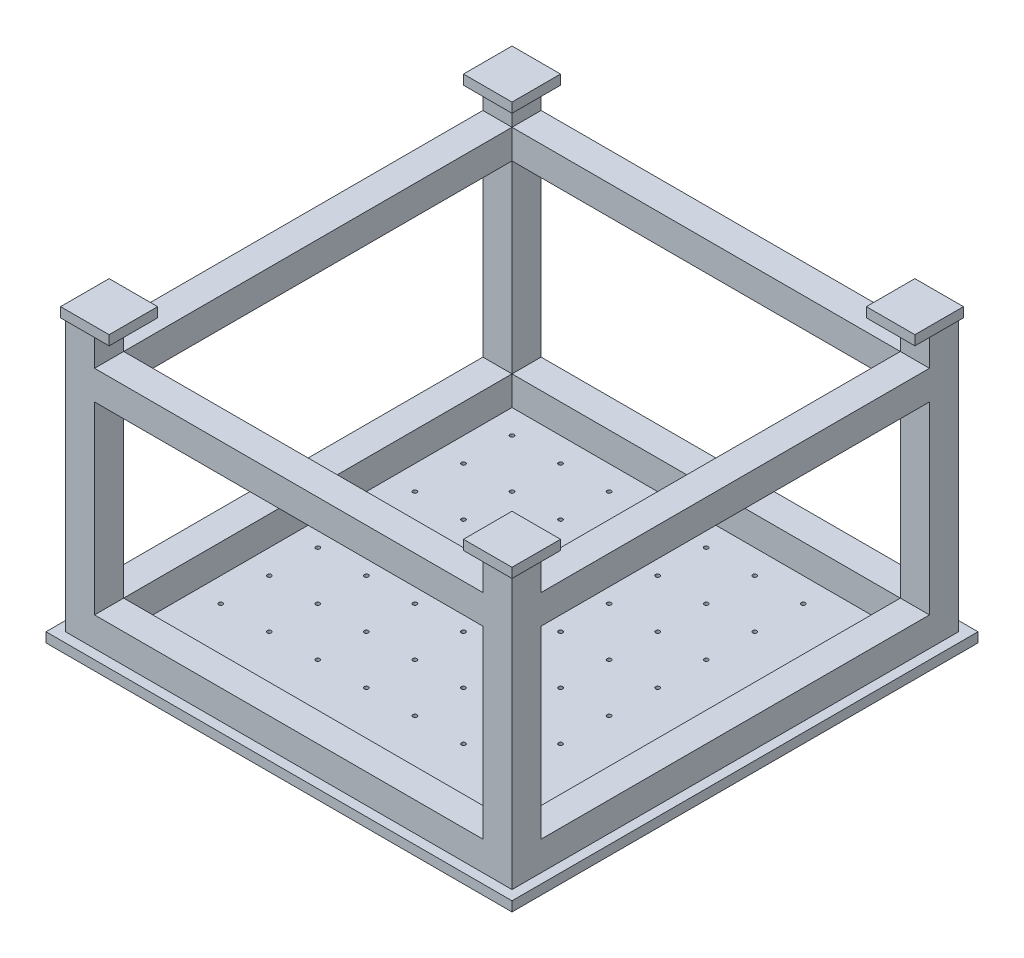
SolidWorks part; units mm, degrees
ref_plane "Front Plane" through (0, 0, 0) normal (0, 0, 1) x (1, 0, 0)
ref_plane "Top Plane" through (0, 0, 0) normal (0, 1, 0) x (1, 0, 0)
ref_plane "Right Plane" through (0, 0, 0) normal (1, 0, 0) x (0, 0, -1)
sketch "Sketch1" plane through (0, 0, 0) normal (0, 1, 0) x (1, 0, 0)
  line L0 (0, 609.6) -> (1219.2, 609.6) construction
  line L1 (0, 0) -> (1219.2, 0)
  line L2 (0, 0) -> (0, 1219.2)
  line L3 (0, 1219.2) -> (1219.2, 1219.2)
  line L4 (1219.2, 0) -> (1219.2, 1219.2)
  dimension "D1" = 1219.2
  dimension "D2" = 1219.2
extrude "Boss-Extrude1" add sketch "Sketch1" along normal blind 25.4
sketch "Sketch2" plane through (0, 25.4, 0) normal (0, 1, 0) x (1, 0, 0)
  line L0 (1219.2, 1219.2) -> (0, 1219.2) construction
  line L1 (25.4, 1193.8) -> (101.6, 1193.8)
  line L2 (25.4, 1193.8) -> (25.4, 1117.6)
  line L3 (25.4, 1117.6) -> (101.6, 1117.6)
  line L4 (101.6, 1193.8) -> (101.6, 1117.6)
  line L5 (0, 1219.2) -> (0, 0) construction
  line L6 (609.6, 1219.2) -> (609.6, 0) construction
  line L7 (-156.4826, 0) -> (156.4826, 0) construction
  line L8 (0, 609.6) -> (1219.2, 609.6) construction
  line L9 (1219.2, 0) -> (1219.2, 1219.2) construction
  line L10 (1117.6, 1193.8) -> (1117.6, 1117.6)
  line L11 (1193.8, 1117.6) -> (1117.6, 1117.6)
  line L12 (1193.8, 1193.8) -> (1193.8, 1117.6)
  line L13 (1193.8, 1193.8) -> (1117.6, 1193.8)
  line L14 (1193.8, 25.4) -> (1117.6, 25.4)
  line L15 (1193.8, 25.4) -> (1193.8, 101.6)
  line L16 (1193.8, 101.6) -> (1117.6, 101.6)
  line L17 (1117.6, 25.4) -> (1117.6, 101.6)
  line L18 (101.6, 25.4) -> (101.6, 101.6)
  line L19 (25.4, 101.6) -> (101.6, 101.6)
  line L20 (25.4, 25.4) -> (25.4, 101.6)
  line L21 (25.4, 25.4) -> (101.6, 25.4)
  dimension "D1" = 76.2
  dimension "D2" = 76.2
  dimension "D3" = 25.4
  dimension "D4" = 25.4
extrude "Boss-Extrude2" add sketch "Sketch2" along normal blind 711.2
sketch "Sketch3" plane through (0, 0, -101.6) normal (0, 0, -1) x (-1, 0, 0)
  line L0 (-101.6, 736.6) -> (-101.6, 25.4) construction
  line L1 (-25.4, 25.4) -> (-101.6, 25.4)
  line L2 (-25.4, 25.4) -> (-25.4, 101.6)
  line L3 (-25.4, 101.6) -> (-101.6, 101.6)
  line L4 (-101.6, 25.4) -> (-101.6, 101.6)
  line L5 (-1193.8, 736.6) -> (-1193.8, 25.4) construction
  line L6 (-1117.6, 25.4) -> (-1193.8, 25.4)
  line L7 (-1117.6, 25.4) -> (-1117.6, 101.6)
  line L8 (-1117.6, 101.6) -> (-1193.8, 101.6)
  line L9 (-1193.8, 25.4) -> (-1193.8, 101.6)
  line L10 (-25.4, 736.6) -> (-25.4, 25.4) construction
  line L11 (-25.4, 584.2) -> (-101.6, 584.2)
  line L12 (-25.4, 584.2) -> (-25.4, 660.4)
  line L13 (-25.4, 660.4) -> (-101.6, 660.4)
  line L14 (-101.6, 584.2) -> (-101.6, 660.4)
  line L15 (-1117.6, 736.6) -> (-1117.6, 25.4) construction
  line L16 (-1117.6, 584.2) -> (-1193.8, 584.2)
  line L17 (-1117.6, 584.2) -> (-1117.6, 660.4)
  line L18 (-1117.6, 660.4) -> (-1193.8, 660.4)
  line L19 (-1193.8, 584.2) -> (-1193.8, 660.4)
  line L20 (-101.6, 736.6) -> (-25.4, 736.6) construction
  dimension "D1" = 76.2
  dimension "D2" = 76.2
  dimension "D3" = 76.2
extrude "Boss-Extrude3" add sketch "Sketch3" along normal up to next
sketch "Sketch4" plane through (1117.6, 0, 0) normal (-1, 0, 0) x (0, 0, 1)
  line L0 (-1117.6, 101.6) -> (-101.6, 101.6) construction
  line L1 (-25.4, 25.4) -> (-101.6, 25.4)
  line L2 (-25.4, 25.4) -> (-25.4, 101.6)
  line L3 (-25.4, 101.6) -> (-101.6, 101.6)
  line L4 (-101.6, 25.4) -> (-101.6, 101.6)
  line L5 (-1193.8, 25.4) -> (-1117.6, 25.4)
  line L6 (-1193.8, 25.4) -> (-1193.8, 101.6)
  line L7 (-1193.8, 101.6) -> (-1117.6, 101.6)
  line L8 (-1117.6, 25.4) -> (-1117.6, 101.6)
  line L9 (-25.4, 736.6) -> (-25.4, 25.4) construction
  line L10 (-101.6, 584.2) -> (-25.4, 584.2)
  line L11 (-101.6, 584.2) -> (-101.6, 660.4)
  line L12 (-101.6, 660.4) -> (-25.4, 660.4)
  line L13 (-25.4, 584.2) -> (-25.4, 660.4)
  line L14 (-1193.8, 736.6) -> (-1193.8, 25.4) construction
  line L15 (-1117.6, 584.2) -> (-1193.8, 584.2)
  line L16 (-1117.6, 584.2) -> (-1117.6, 660.4)
  line L17 (-1117.6, 660.4) -> (-1193.8, 660.4)
  line L18 (-1193.8, 584.2) -> (-1193.8, 660.4)
  line L19 (-1117.6, 660.4) -> (-101.6, 660.4) construction
extrude "Boss-Extrude4" add sketch "Sketch4" along normal up to next
sketch "Sketch5" plane through (0, 736.6, 0) normal (0, 1, 0) x (1, 0, 0)
  line L0 (25.4, 101.6) -> (25.4, 25.4) construction
  line L1 (19.05, 19.05) -> (146.05, 19.05)
  line L2 (19.05, 19.05) -> (19.05, 146.05)
  line L3 (19.05, 146.05) -> (146.05, 146.05)
  line L4 (146.05, 19.05) -> (146.05, 146.05)
  line L5 (25.4, 25.4) -> (101.6, 25.4) construction
  line L6 (25.4, 1193.8) -> (1193.8, 1193.8) construction
  line L7 (609.6, 1193.8) -> (609.6, 25.4) construction
  line L8 (1073.15, 19.05) -> (1073.15, 146.05)
  line L9 (1200.15, 146.05) -> (1073.15, 146.05)
  line L10 (1200.15, 19.05) -> (1200.15, 146.05)
  line L11 (1200.15, 19.05) -> (1073.15, 19.05)
  line L12 (609.6, 609.6) -> (1193.8, 609.6) construction
  line L13 (1200.15, 1200.15) -> (1073.15, 1200.15)
  line L14 (1200.15, 1200.15) -> (1200.15, 1073.15)
  line L15 (1200.15, 1073.15) -> (1073.15, 1073.15)
  line L16 (1073.15, 1200.15) -> (1073.15, 1073.15)
  line L17 (146.05, 1200.15) -> (146.05, 1073.15)
  line L18 (19.05, 1073.15) -> (146.05, 1073.15)
  line L19 (19.05, 1200.15) -> (19.05, 1073.15)
  line L20 (19.05, 1200.15) -> (146.05, 1200.15)
  line L21 (1193.8, 25.4) -> (1193.8, 101.6) construction
  dimension "D1" = 127
  dimension "D2" = 127
  dimension "D3" = 6.35
  dimension "D4" = 6.35
extrude "Boss-Extrude5" add sketch "Sketch5" along normal blind 25.4
hole_wizard "1/2-13 Tapped Hole1" positions "Sketch6" profile "Sketch7" tap size "1/2-13" standard "ANSI Inch" end condition through all
sketch "Sketch6" plane through (0, 0, 0) normal (0, -1, 0) x (-1, 0, 0)
  line L0 (-609.6, 0) -> (-609.6, 1219.2) construction
  line L1 (0, 0) -> (-1219.2, 0) construction
  line L2 (-1219.2, 1219.2) -> (0, 1219.2) construction
  line L3 (0, 609.6) -> (-1219.2, 609.6) construction
  line L4 (0, 1219.2) -> (0, 0) construction
  line L5 (-1219.2, 0) -> (-1219.2, 1219.2) construction
  point P0 (-673.1, 546.1)
  point P25 (-546.1, 546.1)
  point P26 (-419.1, 546.1)
  point P27 (-292.1, 546.1)
  point P28 (-165.1, 546.1)
  point P30 (-546.1, 419.1)
  point P31 (-419.1, 419.1)
  point P32 (-292.1, 419.1)
  point P33 (-165.1, 419.1)
  point P35 (-546.1, 292.1)
  point P36 (-419.1, 292.1)
  point P37 (-292.1, 292.1)
  point P38 (-165.1, 292.1)
  point P40 (-546.1, 165.1)
  point P41 (-419.1, 165.1)
  point P42 (-292.1, 165.1)
  point P43 (-165.1, 165.1)
  point P50 (-673.1, 419.1)
  point P51 (-673.1, 292.1)
  point P52 (-673.1, 165.1)
  point P54 (-165.1, 673.1)
  point P55 (-673.1, 1054.1)
  point P56 (-673.1, 927.1)
  point P57 (-673.1, 800.1)
  point P58 (-165.1, 1054.1)
  point P59 (-292.1, 1054.1)
  point P60 (-419.1, 1054.1)
  point P61 (-546.1, 1054.1)
  point P62 (-165.1, 927.1)
  point P63 (-292.1, 927.1)
  point P64 (-419.1, 927.1)
  point P65 (-546.1, 927.1)
  point P66 (-165.1, 800.1)
  point P67 (-292.1, 800.1)
  point P68 (-419.1, 800.1)
  point P69 (-546.1, 800.1)
  point P70 (-292.1, 673.1)
  point P71 (-419.1, 673.1)
  point P72 (-546.1, 673.1)
  point P73 (-673.1, 673.1)
  point P74 (-800.1, 673.1)
  point P75 (-927.1, 673.1)
  point P76 (-800.1, 800.1)
  point P77 (-927.1, 800.1)
  point P78 (-1054.1, 800.1)
  point P79 (-800.1, 927.1)
  point P80 (-927.1, 927.1)
  point P81 (-1054.1, 927.1)
  point P82 (-800.1, 1054.1)
  point P83 (-927.1, 1054.1)
  point P84 (-1054.1, 1054.1)
  point P85 (-1054.1, 673.1)
  point P86 (-1054.1, 165.1)
  point P87 (-927.1, 165.1)
  point P88 (-800.1, 165.1)
  point P89 (-1054.1, 292.1)
  point P90 (-927.1, 292.1)
  point P91 (-800.1, 292.1)
  point P92 (-1054.1, 419.1)
  point P93 (-927.1, 419.1)
  point P94 (-800.1, 419.1)
  point P95 (-1054.1, 546.1)
  point P96 (-927.1, 546.1)
  point P97 (-800.1, 546.1)
  dimension "D1" = 63.5
  dimension "D2" = 63.5
  dimension "D3" = 5
  dimension "D4" = 4
sketch "Sketch7" plane through (673.1, 0, -546.1) normal (1, 0, 0) x (0, 0, -1)
  line L0 (0, 0) -> (0, 762)
  line L1 (0, 762) -> (5.3581, 762)
  line L2 (5.3581, 762) -> (5.3581, 0)
  line L5 (5.3581, 0) -> (0, 0)
  line L11 (0, -6.35) -> (0, 107.95) construction
  dimension "Thread Major Dia." = 10.7163
  dimension "Thru Tap Drill Depth" = 762
